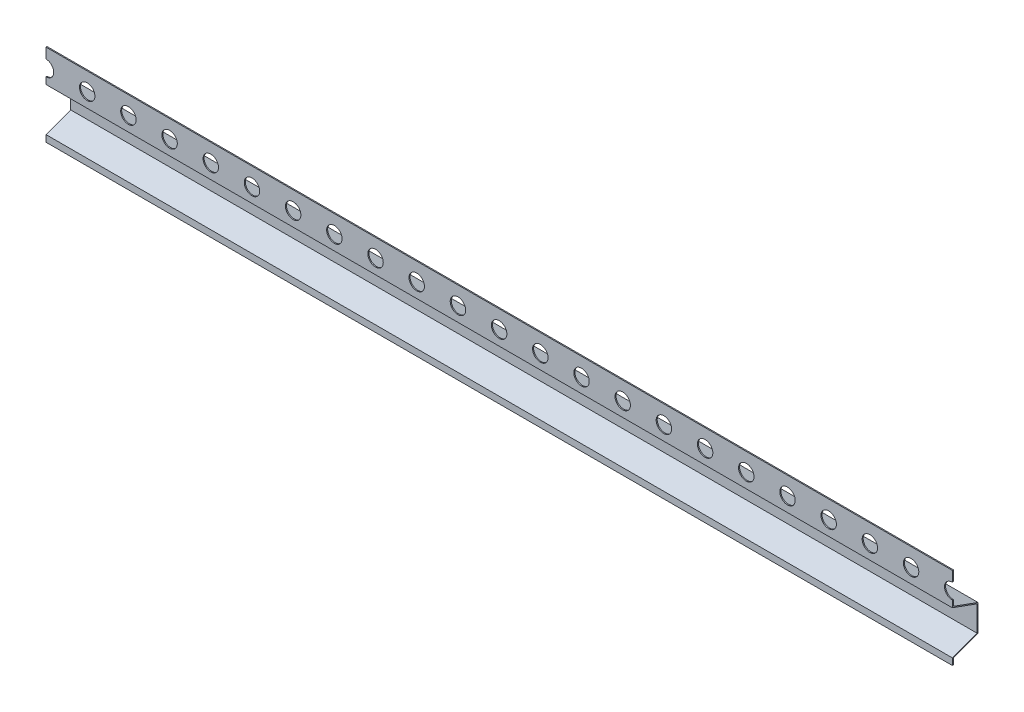
SolidWorks part; units mm, degrees
ref_plane "Top" through (0, 0, 0) normal (0, 0, 1) x (1, 0, 0)
ref_plane "Front" through (0, 0, 0) normal (0, 1, 0) x (1, 0, 0)
ref_plane "Right" through (0, 0, 0) normal (1, 0, 0) x (0, 0, -1)
sketch "Top Sketch" plane through (0, 0, 0) normal (0, 0, 1) x (1, 0, 0)
  line L1 (-88, 0) -> (0, 0)
  line L2 (-88, 0) -> (-88, -8)
  line L3 (-88, -8) -> (0, -8)
  line L4 (0, 0) -> (0, -8)
  dimension "D1" = 88
  dimension "D2" = 8
extrude "Thickness Extrude" add sketch "Top Sketch" against normal blind 0.1
sketch "Pin Hole Sketch" plane through (0, 0, 0) normal (0, 0, 1) x (1, 0, 0)
  line L0 (0, 0) -> (-88, 0) construction
  line L2 (0, -8) -> (0, 0) construction
  circle A0 centre (0, -1.75) radius 0.75
  dimension "D1" = 1.5
  dimension "D2" = 1.75
extrude "First Pin Hole Cut" cut sketch "Pin Hole Sketch" against normal through all
pattern_linear "Pin Hole Pattern" count 23 spacing 4 along (-1, 0, 0) of "First Pin Hole Cut"
sketch "Pocket Sketch" plane through (0, 0, 0) normal (1, 0, 0) x (0, 0, -1)
  line L0 (0, -3.145) -> (2.4, -4.0185)
  line L1 (0, -8) -> (0, -2.5) construction
  line L2 (2.4, -4.0185) -> (2.4, -6.4815)
  line L3 (2.4, -6.4815) -> (0, -7.355)
  line L4 (0.1, -3.075) -> (2.5, -3.9485)
  line L5 (0.1, -8) -> (0.1, -2.5) construction
  line L6 (2.5, -3.9485) -> (2.5, -6.5515)
  line L7 (2.5, -6.5515) -> (0.1, -7.425)
  line L8 (2.4, -5.25) -> (0, -5.25) construction
  line L9 (0.1, -3.075) -> (0, -3.145)
  line L10 (0, -7.355) -> (0.1, -7.425)
  dimension "D1" = 5.25
  dimension "D2" = 0.1
  dimension "D3" = 0.1
  dimension "D4" = 0.1
  dimension "D5" = 110
  dimension "Pocket Width" = 4.35
  dimension "D6" = 110
  dimension "D7" = 2.5
sketch "Pocket Cut Out Sketch" plane through (0, 0, 0) normal (1, 0, 0) x (0, 0, -1)
  line L0 (0, -3.145) -> (0, -7.355)
  line L1 (0, -7.355) -> (2.4, -6.4815)
  line L2 (2.4, -6.4815) -> (2.4, -4.0185)
  line L3 (2.4, -4.0185) -> (0, -3.145)
extrude "Pocket Cut Out" cut sketch "Pocket Cut Out Sketch" against normal through all
extrude "Pocket" add sketch "Pocket Sketch" against normal through all
